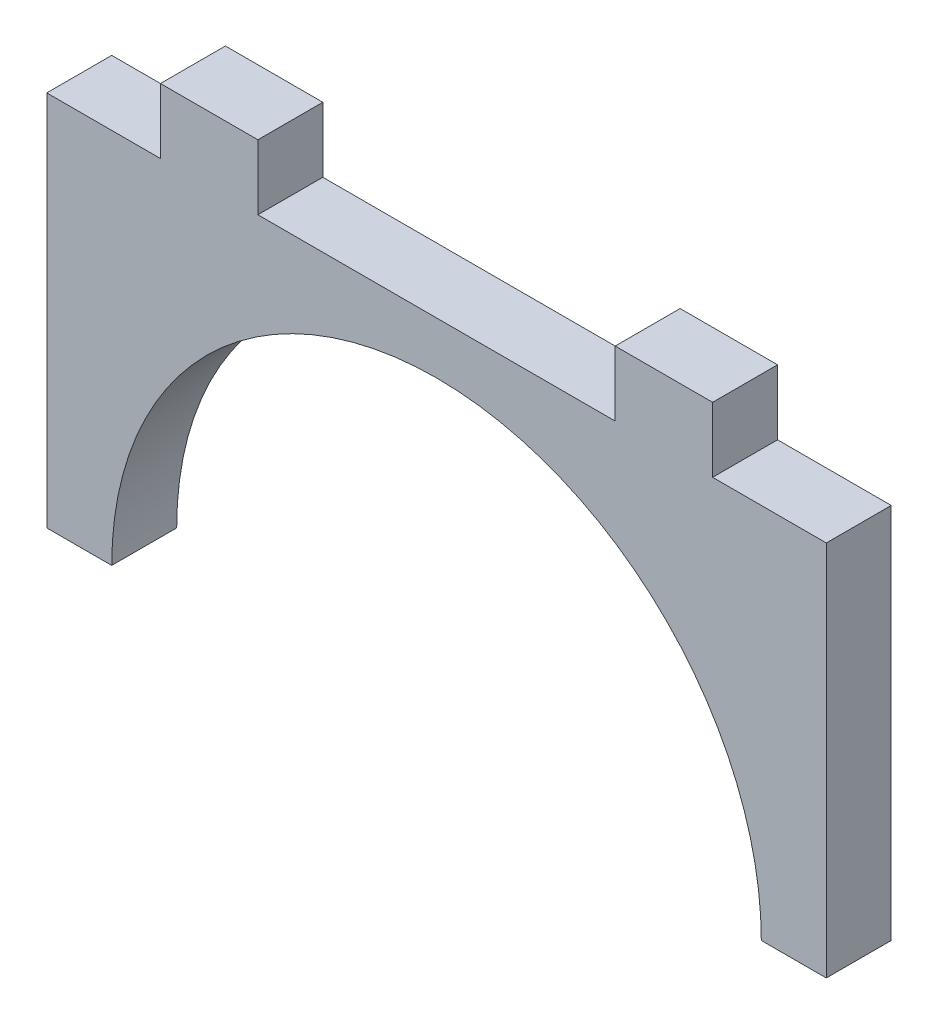
SolidWorks part; units mm, degrees
material "Acrylic (Medium-high impact)"
ref_plane "Front Plane" through (0, 0, 0) normal (0, 0, 1) x (1, 0, 0)
ref_plane "Top Plane" through (0, 0, 0) normal (0, 1, 0) x (1, 0, 0)
ref_plane "Right Plane" through (0, 0, 0) normal (1, 0, 0) x (0, 0, -1)
sketch "Sketch1" plane through (0, 0, 0) normal (0, 0, 1) x (1, 0, 0)
  line L0 (-34.925, 215.9) -> (-34.925, 228.6) construction
  line L1 (76.2, 142.24) -> (63.5, 142.24)
  line L2 (76.2, 142.24) -> (76.2, 215.9)
  line L3 (76.2, 215.9) -> (53.975, 215.9)
  line L4 (-76.2, 142.24) -> (-76.2, 215.9)
  line L5 (-53.975, 215.9) -> (-53.975, 228.6) construction
  line L6 (-63.5, 142.24) -> (-76.2, 142.24)
  line L7 (-53.975, 228.6) -> (-34.925, 228.6) construction
  line L8 (34.925, 215.9) -> (34.925, 228.6) construction
  line L9 (34.925, 228.6) -> (53.975, 228.6) construction
  line L10 (53.975, 215.9) -> (53.975, 228.6) construction
  line L11 (-34.925, 215.9) -> (-34.925, 228.6)
  line L12 (-53.975, 215.9) -> (-53.975, 228.6)
  line L13 (-53.975, 228.6) -> (-34.925, 228.6)
  line L14 (34.925, 215.9) -> (34.925, 228.6)
  line L15 (34.925, 228.6) -> (53.975, 228.6)
  line L16 (53.975, 215.9) -> (53.975, 228.6)
  line L17 (34.925, 215.9) -> (-34.925, 215.9)
  line L18 (-53.975, 215.9) -> (-76.2, 215.9)
  arc A0 (63.5, 142.24) -> (-63.5, 142.24) centre (0, 142.24) ccw
  arc A1 (0, 78.74) -> (63.5, 142.24) centre (0, 142.24) ccw construction
extrude "Extrude1" add sketch "Sketch1" against normal blind 12.7 contours A0 L1 L2 L3 L4 L6
